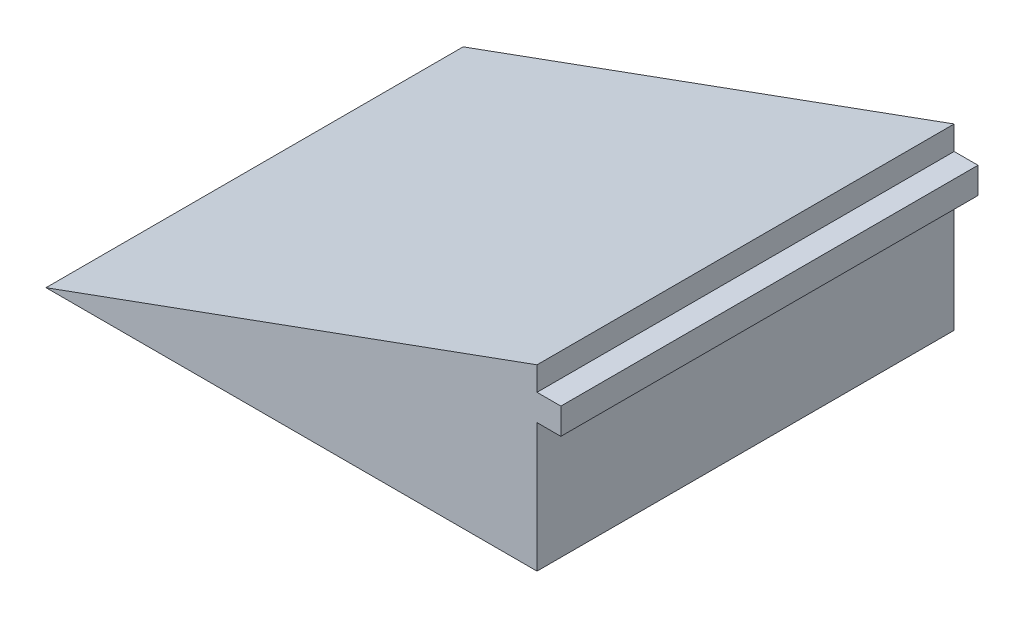
SolidWorks part; units mm, degrees
ref_plane "Front Plane" through (0, 0, 0) normal (0, 0, 1) x (1, 0, 0)
ref_plane "Top Plane" through (0, 0, 0) normal (0, 1, 0) x (1, 0, 0)
ref_plane "Right Plane" through (0, 0, 0) normal (1, 0, 0) x (0, 0, -1)
sketch "Sketch1" plane through (0, 0, 0) normal (0, 0, 1) x (1, 0, 0)
  line L0 (0, 0) -> (412, 0)
  line L1 (412, 0) -> (412, 149.9557)
  line L2 (412, 149.9557) -> (0, 0)
  dimension "D1" = 412
  dimension "D2" = 149.9557
extrude "Boss-Extrude1" add sketch "Sketch1" along normal blind 350
sketch "Sketch2" plane through (412, 0, 0) normal (1, 0, 0) x (0, 0, -1)
  line L0 (-350, 0) -> (-350, 149.9557) construction
  line L1 (-350, 129.9557) -> (0, 129.9557)
  line L2 (-350, 129.9557) -> (-350, 107.9557)
  line L3 (-350, 107.9557) -> (0, 107.9557)
  line L4 (0, 129.9557) -> (0, 107.9557)
  line L5 (0, 0) -> (0, 149.9557) construction
  dimension "D1" = 20
  dimension "D2" = 22
extrude "Boss-Extrude2" add sketch "Sketch2" along normal blind 20
sketch "Sketch3" plane through (0, 0, 0) normal (-0.342, 0.9397, 0) x (0.9397, 0.342, 0)
  line L0 (438.4412, -350) -> (438.4412, 0) construction
  line L1 (438.4412, -190) -> (0, -190)
  line L2 (438.4412, -190) -> (438.4412, -160)
  line L3 (438.4412, -160) -> (0, -160)
  line L4 (0, -190) -> (0, -160)
  line L5 (0, -350) -> (0, 0) construction
  dimension "D1" = 30
  dimension "D2" = 160
